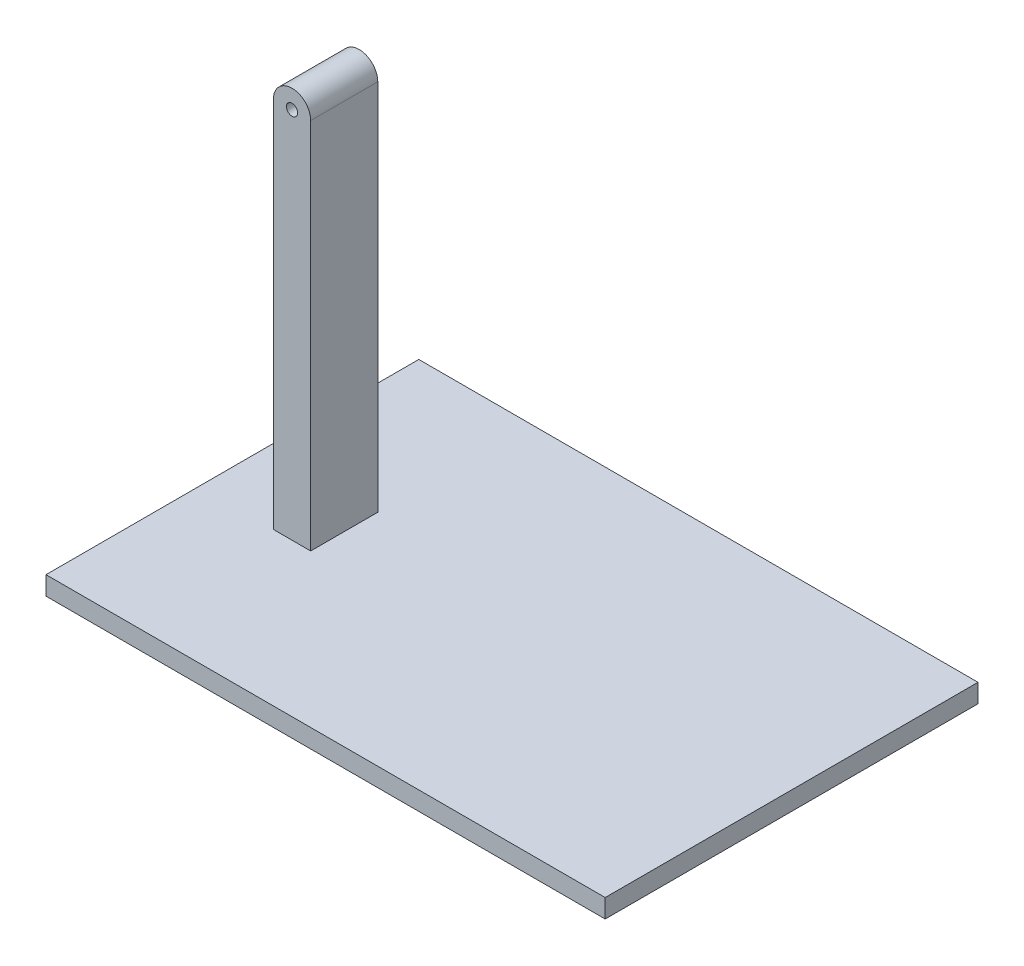
SolidWorks part; units mm, degrees
ref_plane "Front Plane" through (0, 0, 0) normal (0, 0, 1) x (1, 0, 0)
ref_plane "Top Plane" through (0, 0, 0) normal (0, 1, 0) x (1, 0, 0)
ref_plane "Right Plane" through (0, 0, 0) normal (1, 0, 0) x (0, 0, -1)
sketch "Sketch1" plane through (0, 0, 0) normal (0, 1, 0) x (1, 0, 0)
  line L1 (-12.7, 12.7) -> (12.7, 12.7)
  line L2 (-12.7, 12.7) -> (-12.7, -12.7)
  line L3 (-12.7, -12.7) -> (12.7, -12.7)
  line L5 (-12.7, 12.7) -> (12.7, -12.7) construction
  line L6 (-12.7, -12.7) -> (12.7, 12.7) construction
  line L7 (12.7, 12.7) -> (25.4, 12.7)
  line L9 (12.7, -12.7) -> (25.4, -12.7)
  line L10 (25.4, 12.7) -> (25.4, -12.7)
  point P0 (0, 0)
  point P9 (-12.7, 0)
  dimension "D1" = 25.4
  dimension "D2" = 25.4
  dimension "D3" = 38.1
extrude "Boss-Extrude1" add sketch "Sketch1" along normal blind 1.27
sketch "Sketch2" plane through (0, 1.27, 0) normal (0, 1, 0) x (1, 0, 0)
  line L0 (-12.7, 12.7) -> (-12.7, -12.7) construction
  line L1 (-7.62, -2.286) -> (-5.08, -2.286)
  line L2 (-7.62, -2.286) -> (-7.62, 2.286)
  line L3 (-7.62, 2.286) -> (-5.08, 2.286)
  line L4 (-5.08, -2.286) -> (-5.08, 2.286)
  line L5 (-7.62, -2.286) -> (-5.08, 2.286) construction
  line L6 (-7.62, 2.286) -> (-5.08, -2.286) construction
  point P0 (-6.35, 0)
  dimension "D1" = 2.54
  dimension "D2" = 4.572
  dimension "D3" = 5.08
extrude "Boss-Extrude2" add sketch "Sketch2" along normal blind 25.4
sketch "Sketch3" plane through (0, 0, 2.286) normal (0, 0, 1) x (1, 0, 0)
  line L1 (-7.62, 26.67) -> (-5.08, 26.67) construction
  line L2 (-7.62, 26.67) -> (-7.62, 1.27) construction
  circle A0 centre (-6.35, 26.67) radius 1.27
  point P6 (-6.35, 26.67)
extrude "Boss-Extrude3" add sketch "Sketch3" against normal up to surface (4.572 mm away) up to face at (-6.35, 13.97, -2.286)
sketch "Sketch4" plane through (0, 0, 2.286) normal (0, 0, 1) x (1, 0, 0)
  circle A0 centre (-6.35, 26.67) radius 0.381
  arc A1 (-5.08, 26.67) -> (-7.62, 26.67) centre (-6.35, 26.67) ccw construction
  dimension "D1" = 0.762
extrude "Cut-Extrude1" cut sketch "Sketch4" against normal up to surface (4.572 mm away) up to face at (-6.35, 14.2875, -2.286)
